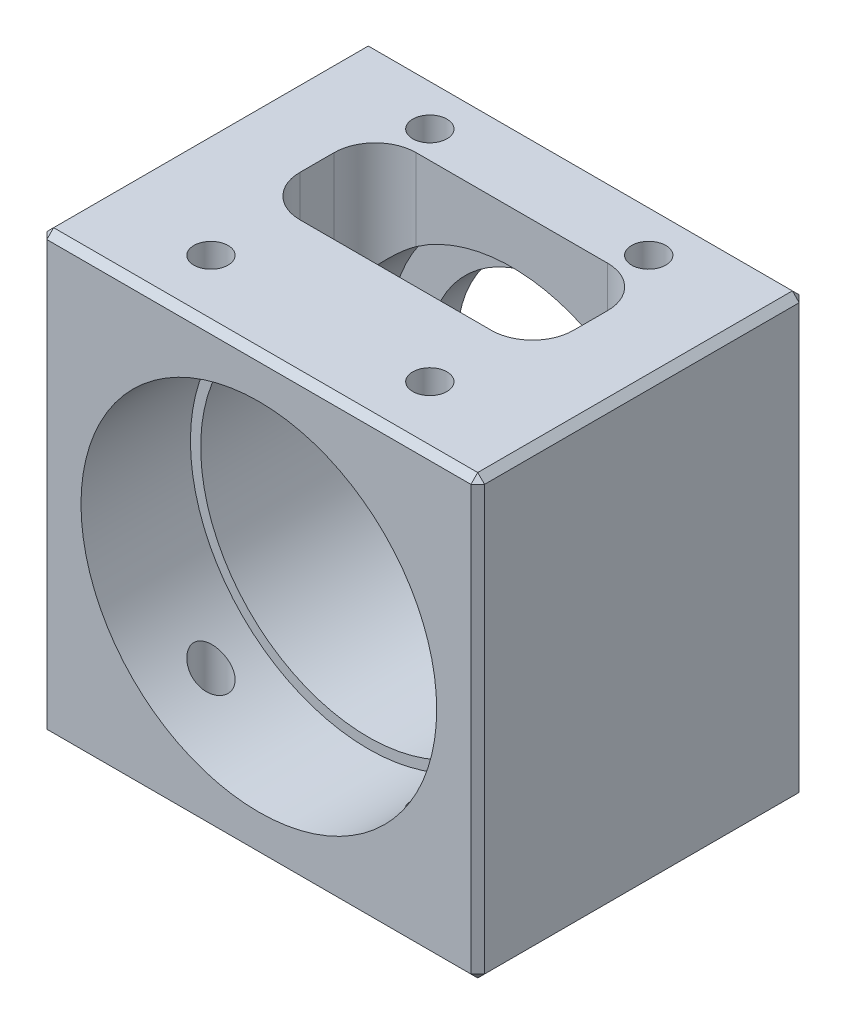
SolidWorks part; units mm, degrees
material "6061 合金"
ref_plane "前视基准面" through (0, 0, 0) normal (0, 0, 1) x (1, 0, 0)
ref_plane "上视基准面" through (0, 0, 0) normal (0, 1, 0) x (1, 0, 0)
ref_plane "右视基准面" through (0, 0, 0) normal (1, 0, 0) x (0, 0, -1)
sketch "草图1" plane through (0, 0, 0) normal (0, 0, 1) x (1, 0, 0)
  circle A0 centre (0, 0) radius 12.5 construction
  circle A1 centre (0, 0) radius 6.65
  circle A2 centre (0, 0) radius 16
  dimension "D1" = 13.3
  dimension "D2" = 25
  dimension "D3" = 32
  dimension "D4" = 3.5
extrude "凸台-拉伸1" add sketch "草图1" along normal blind 24
sketch "草图3" plane through (0, 0, 0) normal (0, 0, -1) x (-1, 0, 0)
  circle A0 centre (0, 0) radius 9.5 construction
  circle A1 centre (0, 9.5) radius 1.5
  dimension "D1" = 19
  dimension "D2" = 3
extrude "切除-拉伸2" cut sketch "草图3" against normal through all
pattern_circular "阵列(圆周)1" count 6 over 360 about axis through (0, 0, 0) along (0, 0, 1) of "切除-拉伸2"
sketch "草图4" plane through (0, 0, 24) normal (0, 0, 1) x (1, 0, 0)
  line L0 (0, 0) -> (0, -16) construction
  line L1 (-16, 0) -> (-16, -16)
  line L2 (0, 0) -> (-16, 0) construction
  line L3 (-16, -16) -> (16, -16)
  line L4 (-16, 0) -> (-16, -17.3228) construction
  line L5 (16, 16) -> (16, -16)
  line L6 (-6.65, 0) -> (-16, 0)
  line L7 (6.65, 0) -> (16, 0)
  line L8 (-16, 0) -> (-16, 16)
  line L9 (-16, 16) -> (16, 16)
  circle A0 centre (0, 0) radius 16 construction
  circle A1 centre (8.2272, -4.75) radius 1.5 construction
  circle A2 centre (0, 0) radius 6.65 construction
  arc A3 (-6.65, 0) -> (6.65, 0) centre (0, 0) ccw
  circle A4 centre (0, -9.5) radius 1.5 construction
  circle A5 centre (-8.2272, -4.75) radius 1.5 construction
  circle A6 centre (8.2272, -4.75) radius 1.5
  circle A7 centre (0, -9.5) radius 1.5
  circle A8 centre (-8.2272, -4.75) radius 1.5
  circle A9 centre (0, 0) radius 9.5
  circle M5 centre (0, 0) radius 16
extrude "凸台-拉伸2" add sketch "草图4" against normal up to surface (24 mm away) contours L5 L3 M5 | L1 L3 M5 | L9 L8 M5 | L9 L5 M5 up to face at (8.9772, -3.451, 0)
sketch "草图7" plane through (0, 0, 24) normal (0, 0, 1) x (1, 0, 0)
  circle A0 centre (0, 0) radius 13
  dimension "D1" = 26
extrude "切除-拉伸3" cut sketch "草图7" against normal offset from surface (21.8 mm away) 2.2 up to face at (8.9772, -3.451, 0)
ref_plane "基准面1" through (16, -16, 0) normal (1, 0, 0) x (0, 0, -1)
sketch "草图15" plane through (0, 0, 2.2) normal (0, 0, 1) x (1, 0, 0)
  circle A0 centre (0, 0) radius 13
  circle A1 centre (0, 0) radius 12.25
  dimension "D1" = 26
  dimension "D2" = 24.5
extrude "凸台-拉伸4" add sketch "草图15" along normal offset from surface (13.8 mm away) 8 up to face at (13, 0, 24)
sketch "草图11" plane through (0, 16, 0) normal (0, 1, 0) x (1, 0, 0)
  line L0 (0, 0) -> (0, -42.9466) construction
  line L1 (16, 0) -> (-16, 0) construction
  line L2 (-16, -24) -> (16, -24) construction
  line L3 (-10, -14) -> (10, -14)
  line L4 (-10, -14) -> (-10, -5.5)
  line L5 (-10, -5.5) -> (10, -5.5)
  line L6 (10, -14) -> (10, -5.5)
  line L7 (-10, -14) -> (10, -5.5) construction
  line L8 (-10, -5.5) -> (10, -14) construction
  line L9 (16, 0) -> (16, -24) construction
  point P4 (0, -9.75)
  dimension "D1" = 5.5
  dimension "D2" = 10
  dimension "D3" = 6
extrude "切除-拉伸4" cut sketch "草图11" against normal blind 10
fillet "圆角1" radius 3 4 edges at (-10, 11.5377, 14) (10, 11.5377, 14) (10, 11.5377, 5.5) (-10, 11.5377, 5.5)
sketch "草图12" plane through (0, 16, 0) normal (0, 1, 0) x (1, 0, 0)
  line L0 (0, 17.576) -> (0, -31.2951) construction
  line L1 (16, 0) -> (-16, 0) construction
  circle A0 centre (8, -3.5) radius 1
  circle A1 centre (8, -19.5) radius 1
  circle A2 centre (-8, -3.5) radius 1
  circle A3 centre (-8, -19.5) radius 1
  dimension "D2" = 2
  dimension "D3" = 16
  dimension "D5" = 16
  dimension "D1" = 3.5
extrude "切除-拉伸5" cut sketch "草图12" against normal through all
hole_wizard "M3 螺纹孔1" positions "草图13" profile "草图14" tap size "M3" standard "GB" end condition through all
sketch "草图13" plane through (0, 16, 0) normal (0, 1, 0) x (1, 0, 0)
  point P0 (8, -3.5)
  point P3 (-8, -3.5)
  point P6 (-8, -19.5)
  point P9 (8, -19.5)
cosmetic thread "孔螺蚊线5" parameters "D2"=3
cosmetic thread "孔螺蚊线6" parameters "D2"=3
cosmetic thread "孔螺蚊线15" parameters "D2"=3
cosmetic thread "孔螺蚊线16" parameters "D2"=3
sketch "草图14" plane through (8, 16, 3.5) normal (1, 0, 0) x (0, 0, 1)
  line L0 (0, 0) -> (0, 32)
  line L1 (0, 32) -> (1.25, 32)
  line L2 (1.25, 32) -> (1.25, 0)
  line L5 (1.25, 0) -> (0, 0)
  line L11 (0, -6.35) -> (0, 107.95) construction
  dimension "通孔螺纹孔钻头直径" = 2.5
  dimension "通孔螺纹孔钻头深度" = 32
chamfer "倒角1" distance 0.5 angle 45 12 edges at (0, -16, 0) (0, -16, 24) (16, 0, 0) (16, 0, 24) (0, 16, 24) (0, 16, 0) (-16, 0, 0) (-16, 0, 24) (-16, 16, 12) (16, 16, 12) (-16, -16, 12) (16, -16, 12)
sketch "草图19" plane through (0, 0, 0) normal (0, 0, -1) x (-1, 0, 0)
  circle A0 centre (0, 0) radius 11
extrude "凸台-拉伸8" add sketch "草图19" against normal blind 24
sketch "草图20" plane through (0, 0, 5.5) normal (0, 0, 1) x (1, 0, 0)
  circle A0 centre (0, 0) radius 11
extrude "切除-拉伸8" cut sketch "草图20" along normal blind 47
sketch "草图21" plane through (0, 0, 2.2) normal (0, 0, 1) x (1, 0, 0)
  circle A0 centre (0, 0) radius 11
extrude "切除-拉伸9" cut sketch "草图21" along normal blind 60
sketch "草图22" plane through (0, 0, 0) normal (0, 0, -1) x (-1, 0, 0)
  circle A0 centre (0, 0) radius 9.5
extrude "切除-拉伸10" cut sketch "草图22" against normal blind 60
